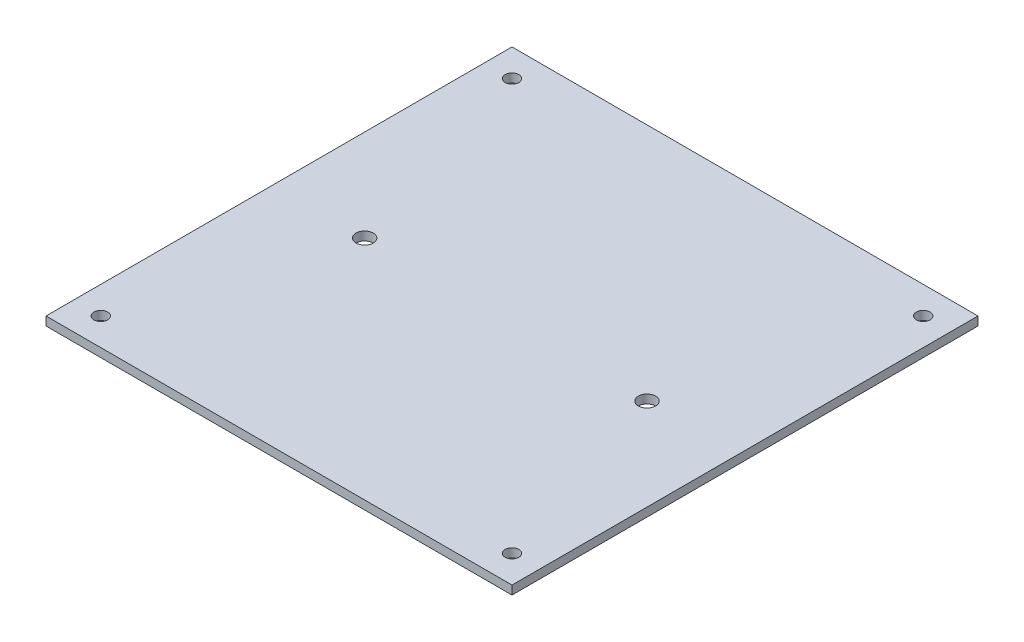
SolidWorks part; units mm, degrees
ref_plane "Front Plane" through (0, 0, 0) normal (0, 0, 1) x (1, 0, 0)
ref_plane "Top Plane" through (0, 0, 0) normal (0, 1, 0) x (1, 0, 0)
ref_plane "Right Plane" through (0, 0, 0) normal (1, 0, 0) x (0, 0, -1)
sketch "Sketch1" plane through (0, 0, 0) normal (0, 1, 0) x (1, 0, 0)
  line L0 (-55, 0) -> (55, 0) construction
  line L1 (-85, -85) -> (85, -85)
  line L2 (-85, -85) -> (-85, 85)
  line L3 (-85, 85) -> (85, 85)
  line L4 (85, -85) -> (85, 85)
  line L5 (-85, -85) -> (85, 85) construction
  line L6 (-85, 85) -> (85, -85) construction
  line L7 (-58.5, -61.25) -> (58.5, -61.25)
  line L8 (-58.5, -61.25) -> (-58.5, 61.25)
  line L9 (-58.5, 61.25) -> (58.5, 61.25)
  line L10 (58.5, -61.25) -> (58.5, 61.25)
  line L11 (-58.5, -61.25) -> (58.5, 61.25) construction
  line L12 (-58.5, 61.25) -> (58.5, -61.25) construction
  line L14 (0, -55) -> (0, 55) construction
  circle A0 centre (-51.5, -2.25) radius 3.15
  circle A1 centre (51.5, -2.25) radius 3.15
  circle A2 centre (-75, 75) radius 2.5
  circle A3 centre (75, 75) radius 2.5
  circle A4 centre (75, -75) radius 2.5
  circle A5 centre (-75, -75) radius 2.5
  point P0 (0, 0)
  point P6 (0, 0)
  dimension "D7" = 6.3
  dimension "D8" = 6.3
  dimension "D10" = 5
  dimension "D11" = 5
  dimension "D1" = 117
  dimension "D2" = 122.5
  dimension "D3" = 170
  dimension "D4" = 170
  dimension "D5" = 103
  dimension "D6" = 63.5
  dimension "D9" = 51.5
  dimension "D12" = 10
  dimension "D13" = 10
extrude "Boss-Extrude1" add sketch "Sketch1" along normal blind 3.175 contours L7 L10 L9 L8 A1 A0 | L1 L4 L3 L2 A4 A3 A2 L10 L7 L8 L9 A5
